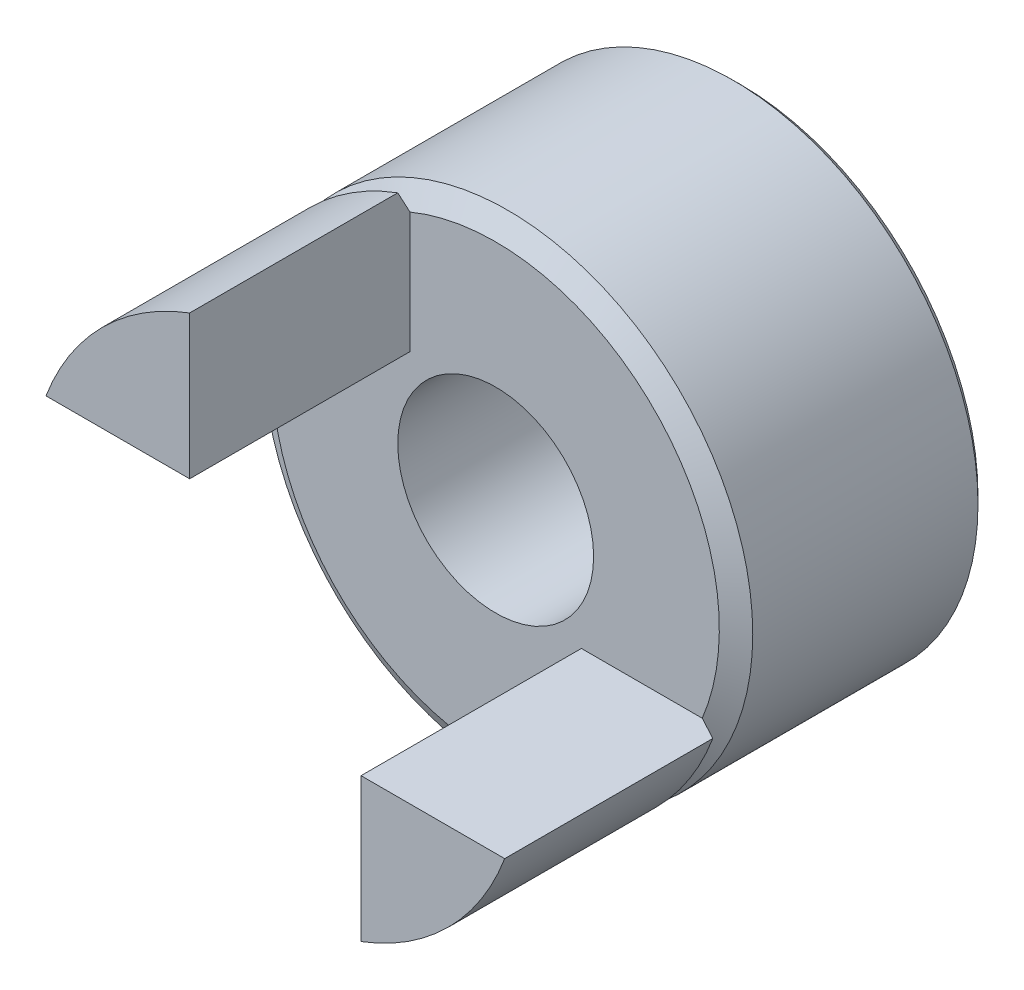
SolidWorks part; units mm, degrees
ref_plane "정면" through (0, 0, 0) normal (0, 0, 1) x (1, 0, 0)
ref_plane "윗면" through (0, 0, 0) normal (0, 1, 0) x (1, 0, 0)
ref_plane "우측면" through (0, 0, 0) normal (1, 0, 0) x (0, 0, -1)
sketch "스케치1" plane through (0, 0, 0) normal (0, 0, 1) x (1, 0, 0)
  circle A0 centre (0, 0) radius 10
  circle A1 centre (0, 0) radius 4
  dimension "D1" = 8
  dimension "D2" = 20
extrude "보스-돌출1" add sketch "스케치1" along normal blind 10
chamfer "모따기1" distance 0.3 angle 45 2 edges at (4, 0, 0) (10, 0, 0)
sketch "스케치2" plane through (0, 0, 10) normal (0, 0, 1) x (1, 0, 0)
  line L1 (-10, -3.5) -> (10, -3.5)
  line L2 (-10, -3.5) -> (-10, 3.5)
  line L3 (-10, 3.5) -> (10, 3.5)
  line L4 (10, -3.5) -> (10, 3.5)
  line L5 (-10, -3.5) -> (10, 3.5) construction
  line L6 (-10, 3.5) -> (10, -3.5) construction
  line L7 (-3.5, -10) -> (3.5, -10)
  line L8 (-3.5, -10) -> (-3.5, 10)
  line L9 (-3.5, 10) -> (3.5, 10)
  line L10 (3.5, -10) -> (3.5, 10)
  line L11 (-3.5, -10) -> (3.5, 10) construction
  line L12 (-3.5, 10) -> (3.5, -10) construction
  circle A1 centre (0, 0) radius 10
  circle A2 centre (0, 0) radius 10
  circle M5 centre (0, 0) radius 10
  dimension "D2" = 7
  dimension "D1" = 0
extrude "보스-돌출2" add sketch "스케치2" along normal blind 9 contours L3 L8 M5 | L10 L1 M5
sketch "스케치3" plane through (0, 0, 0) normal (0, 1, 0) x (1, 0, 0)
  line L1 (9.134, -10) -> (10, -10.5)
  line L2 (10, -10.5) -> (10, -9.5)
  line L3 (10, -9.5) -> (9.134, -10)
  line L7 (0, 0) -> (0, -17.4659) construction
  circle A0 centre (9.7113, -10) radius 0.2887 construction
  dimension "D1" = 10
  dimension "D2" = 1
  dimension "D3" = 9.5
revolve "컷-회전1" cut sketch "스케치3" angle 360 about L7
